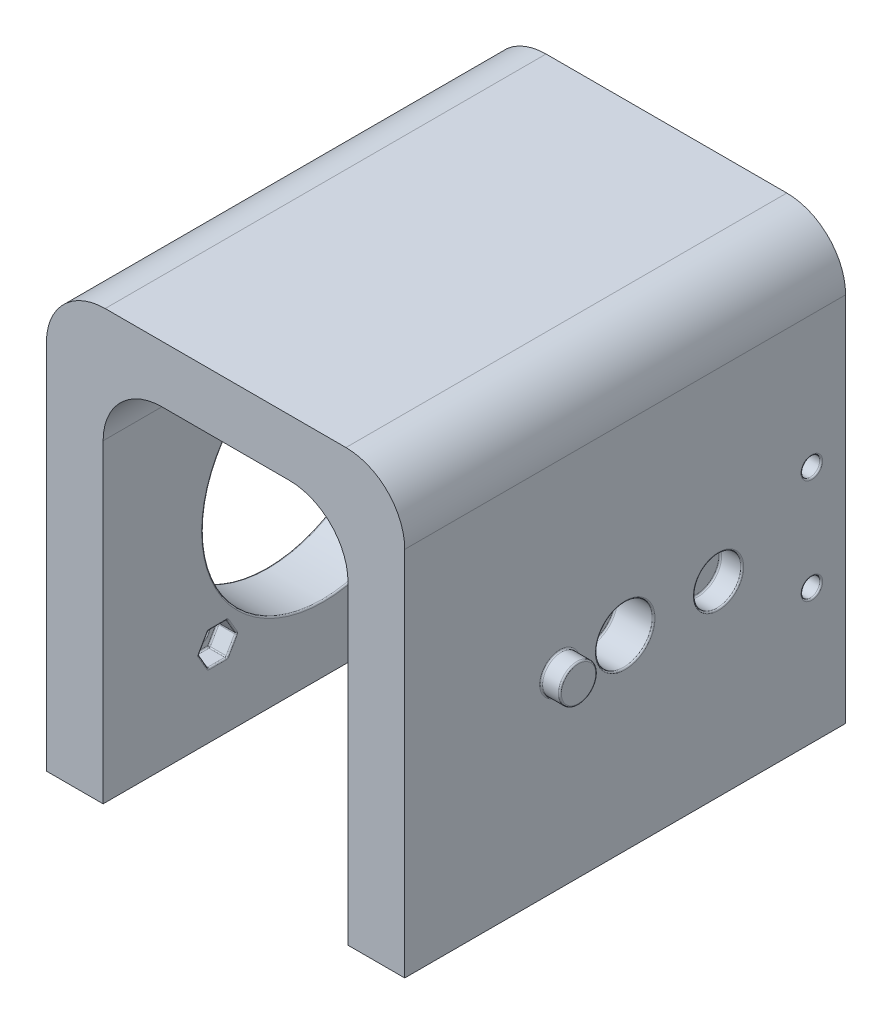
SolidWorks part; units mm, degrees
ref_plane "Front Plane" through (0, 0, 0) normal (0, 0, 1) x (1, 0, 0)
ref_plane "Top Plane" through (0, 0, 0) normal (0, 1, 0) x (1, 0, 0)
ref_plane "Right Plane" through (0, 0, 0) normal (1, 0, 0) x (0, 0, -1)
sketch "Sketch1" plane through (0, 0, 0) normal (0, 0, 1) x (1, 0, 0)
  line L0 (-20.828, 63.5) -> (20.828, 63.5)
  line L1 (20.828, 63.5) -> (20.828, 0)
  line L2 (20.828, 0) -> (30.48, 0)
  line L3 (30.48, 0) -> (30.48, 73.152)
  line L4 (30.48, 73.152) -> (-30.48, 73.152)
  line L5 (-30.48, 73.152) -> (-30.48, 0)
  line L6 (-30.48, 0) -> (-20.828, 0)
  line L7 (-20.828, 0) -> (-20.828, 63.5)
  line L8 (-20.828, 63.5) -> (-20.828, 73.152) construction
  point P2 (0, 63.5)
  point P10 (0, 73.152)
  dimension "D1" = 9.652
  dimension "D2" = 41.656
  dimension "D3" = 63.5
extrude "Boss-Extrude1" add sketch "Sketch1" along normal blind 75
sketch "Sketch2" plane through (-30.48, 0, 0) normal (-1, 0, 0) x (0, 0, 1)
  line L0 (75, 0) -> (0, 0) construction
  line L1 (75, 63.5) -> (0, 63.5) construction
  circle A0 centre (37.5, 31.75) radius 20.5
  point P4 (0, 0)
  point P5 (37.5, 0)
  dimension "D1" = 41
  dimension "D2" = 31.75
extrude "Cut-Extrude1" cut sketch "Sketch2" against normal up to next
sketch "Sketch3" plane through (-30.48, 0, 0) normal (-1, 0, 0) x (0, 0, 1)
  line L1 (19.5, 13.75) -> (55.5, 13.75) construction
  line L2 (19.5, 13.75) -> (19.5, 49.75) construction
  line L3 (19.5, 49.75) -> (55.5, 49.75) construction
  line L4 (55.5, 13.75) -> (55.5, 49.75) construction
  line L5 (19.5, 13.75) -> (55.5, 49.75) construction
  line L6 (19.5, 49.75) -> (55.5, 13.75) construction
  circle A0 centre (37.5, 31.75) radius 20.5 construction
  circle A1 centre (19.5, 49.75) radius 1.5875
  circle A2 centre (55.5, 49.75) radius 1.5875
  circle A3 centre (55.5, 13.75) radius 1.5875
  circle A4 centre (19.5, 13.75) radius 1.5875
  point P0 (37.5, 31.75)
  dimension "D2" = 3.175
  dimension "D1" = 36
extrude "Cut-Extrude2" cut sketch "Sketch3" against normal up to next
sketch "Sketch4" plane through (20.828, 0, 0) normal (-1, 0, 0) x (0, 0, 1)
  circle A0 centre (37.5, 31.75) radius 3.429
  circle A1 centre (37.5, 31.75) radius 20.5 construction
  dimension "D1" = 6.858
extrude "Cut-Extrude3" cut sketch "Sketch4" against normal up to next
sketch "Sketch5" plane through (20.828, 0, 0) normal (-1, 0, 0) x (0, 0, 1)
  circle A0 centre (37.5, 31.75) radius 4.7625
  circle A1 centre (37.5, 31.75) radius 3.429
  circle A2 centre (37.5, 31.75) radius 3.429 construction
  dimension "D1" = 9.525
extrude "Boss-Extrude2" add sketch "Sketch5" along normal blind 1.5875
sketch "Sketch6" plane through (30.48, 0, 0) normal (1, 0, 0) x (0, 0, -1)
  line L0 (-5.75, 40.64) -> (-5.75, 22.86) construction
  line L1 (-37.5, 31.75) -> (-5.75, 31.75) construction
  circle A0 centre (-5.75, 40.64) radius 1.5875
  circle A1 centre (-5.75, 22.86) radius 1.5875
  dimension "D1" = 3.175
  dimension "D2" = 31.75
  dimension "D3" = 8.89
extrude "Cut-Extrude5" cut sketch "Sketch6" against normal up to next
sketch "Sketch7" plane through (30.48, 0, 0) normal (1, 0, 0) x (0, 0, -1)
  line L0 (-37.5, 31.75) -> (-21.625, 31.75) construction
  circle A0 centre (-21.625, 31.75) radius 4.0323
  dimension "D1" = 8.0645
  dimension "D2" = 15.875
extrude "Cut-Extrude6" cut sketch "Sketch7" against normal blind 3.75
sketch "Sketch8" plane through (30.48, 0, 0) normal (1, 0, 0) x (0, 0, -1)
  circle A0 centre (-37.5, 31.75) radius 4.826
  dimension "D1" = 9.652
extrude "Cut-Extrude7" cut sketch "Sketch8" against normal blind 6.35
sketch "Sketch9" plane through (30.48, 0, 0) normal (1, 0, 0) x (0, 0, -1)
  line L0 (-48.6125, 31.75) -> (-37.5, 31.75) construction
  circle A0 centre (-48.6125, 31.75) radius 3.175
  dimension "D1" = 6.35
  dimension "D2" = 11.1125
extrude "Boss-Extrude3" add sketch "Sketch9" along normal blind 3.175
sketch "Sketch10" plane through (20.828, 0, 0) normal (-1, 0, 0) x (0, 0, 1)
  line L1 (8.925, 40.64) -> (7.3375, 43.3896)
  line L2 (7.3375, 43.3896) -> (4.1625, 43.3896)
  line L3 (4.1625, 43.3896) -> (2.575, 40.64)
  line L4 (2.575, 40.64) -> (4.1625, 37.8904)
  line L5 (4.1625, 37.8904) -> (7.3375, 37.8904)
  line L6 (7.3375, 37.8904) -> (8.925, 40.64)
  line L7 (8.925, 22.86) -> (7.3375, 25.6096)
  line L8 (7.3375, 25.6096) -> (4.1625, 25.6096)
  line L9 (4.1625, 25.6096) -> (2.575, 22.86)
  line L10 (2.575, 22.86) -> (4.1625, 20.1104)
  line L11 (4.1625, 20.1104) -> (7.3375, 20.1104)
  line L12 (7.3375, 20.1104) -> (8.925, 22.86)
  circle A0 centre (5.75, 40.64) radius 2.7496 construction
  circle A1 centre (5.75, 22.86) radius 2.7496 construction
  circle A2 centre (5.75, 40.64) radius 1.5875 construction
  circle A3 centre (5.75, 22.86) radius 1.5875 construction
  point P9 (0, 0)
  point P19 (0, 0)
  point P20 (0, 0)
  point P23 (0, 0)
  dimension "D1" = 6.35
extrude "Cut-Extrude8" cut sketch "Sketch10" against normal blind 3.175
sketch "Sketch11" plane through (-30.48, 0, 0) normal (-1, 0, 0) x (0, 0, 1)
  circle A0 centre (19.5, 49.75) radius 2.55
  circle A1 centre (55.5, 49.75) radius 2.55
  circle A2 centre (55.5, 13.75) radius 2.55
  circle A3 centre (19.5, 13.75) radius 2.55
  circle A4 centre (19.5, 49.75) radius 1.5875
  circle A5 centre (55.5, 49.75) radius 1.5875
  circle A6 centre (55.5, 13.75) radius 1.5875
  circle A7 centre (19.5, 13.75) radius 1.5875
  circle A8 centre (19.5, 49.75) radius 1.5875 construction
  circle A9 centre (55.5, 49.75) radius 1.5875 construction
  circle A10 centre (55.5, 13.75) radius 1.5875 construction
  circle A11 centre (19.5, 13.75) radius 1.5875 construction
  dimension "D1" = 5.1
extrude "Boss-Extrude4" add sketch "Sketch11" along normal blind 4.8
sketch "Sketch12" plane through (-20.828, 0, 0) normal (1, 0, 0) x (0, 0, -1)
  line L1 (-16.325, 49.75) -> (-17.9125, 52.4996)
  line L2 (-17.9125, 52.4996) -> (-21.0875, 52.4996)
  line L3 (-21.0875, 52.4996) -> (-22.675, 49.75)
  line L4 (-22.675, 49.75) -> (-21.0875, 47.0004)
  line L5 (-21.0875, 47.0004) -> (-17.9125, 47.0004)
  line L6 (-17.9125, 47.0004) -> (-16.325, 49.75)
  line L7 (-16.325, 13.75) -> (-17.9125, 16.4996)
  line L8 (-17.9125, 16.4996) -> (-21.0875, 16.4996)
  line L9 (-21.0875, 16.4996) -> (-22.675, 13.75)
  line L10 (-22.675, 13.75) -> (-21.0875, 11.0004)
  line L11 (-21.0875, 11.0004) -> (-17.9125, 11.0004)
  line L12 (-17.9125, 11.0004) -> (-16.325, 13.75)
  line L13 (-52.325, 13.75) -> (-53.9125, 16.4996)
  line L14 (-53.9125, 16.4996) -> (-57.0875, 16.4996)
  line L15 (-57.0875, 16.4996) -> (-58.675, 13.75)
  line L16 (-58.675, 13.75) -> (-57.0875, 11.0004)
  line L17 (-57.0875, 11.0004) -> (-53.9125, 11.0004)
  line L18 (-53.9125, 11.0004) -> (-52.325, 13.75)
  line L19 (-52.325, 49.75) -> (-53.9125, 52.4996)
  line L20 (-53.9125, 52.4996) -> (-57.0875, 52.4996)
  line L21 (-57.0875, 52.4996) -> (-58.675, 49.75)
  line L22 (-58.675, 49.75) -> (-57.0875, 47.0004)
  line L23 (-57.0875, 47.0004) -> (-53.9125, 47.0004)
  line L24 (-53.9125, 47.0004) -> (-52.325, 49.75)
  circle A0 centre (-19.5, 49.75) radius 2.7496 construction
  circle A1 centre (-19.5, 13.75) radius 2.7496 construction
  circle A2 centre (-55.5, 13.75) radius 2.7496 construction
  circle A3 centre (-55.5, 49.75) radius 2.7496 construction
  point P28 (0, 0)
  point P37 (0, 0)
  point P38 (0, 0)
  point P39 (0, 0)
  point P40 (0, 0)
  point P42 (0, 0)
  dimension "D1" = 6.35
extrude "Cut-Extrude9" cut sketch "Sketch12" against normal blind 3.175
fillet "Fillet1" radius 10 4 edges at (30.48, 73.152, 37.5) (-30.48, 73.152, 37.5) (20.828, 63.5, 37.5) (-20.828, 63.5, 37.5)
fillet "Fillet2" radius 0.25 27 edges at (19.2405, 31.75, 40.929) (24.003, 22.86, 7.3375) (30.48, 24.4475, 5.75) (24.003, 40.64, 7.3375) (30.48, 42.2275, 5.75) (30.48, 35.7823, 21.625) (26.73, 35.7823, 21.625) (-20.828, 31.75, 58) (30.48, 36.576, 37.5) (24.13, 36.576, 37.5) (33.655, 34.925, 48.6125) (30.48, 28.575, 48.6125) (20.828, 31.75, 32.7375) (19.2405, 31.75, 42.2625) (-30.48, 16.3, 55.5) (-35.28, 11.2, 55.5) (-35.28, 12.1625, 55.5) (-30.48, 16.3, 19.5) (-35.28, 12.1625, 19.5) (-35.28, 11.2, 19.5) (-30.48, 11.25, 37.5) (-30.48, 52.3, 55.5) (-35.28, 48.1625, 55.5) (-30.48, 52.3, 19.5) (-35.28, 48.1625, 19.5) (-35.28, 47.2, 19.5) (-35.28, 47.2, 55.5)
fillet "Fillet3" radius 0.25 112 edges at (20.828, 21.4852, 8.1312) (20.828, 25.6096, 5.75) (20.828, 21.4852, 3.3688) (20.828, 42.0148, 3.3687) (20.828, 37.8904, 5.75) (20.828, 42.0148, 8.1312) (-20.828, 12.3752, 17.1188) (-20.828, 16.4996, 19.5) (-20.828, 12.3752, 21.8812) (-20.828, 12.3752, 57.8812) (-20.828, 12.3752, 53.1188) (-20.828, 16.4996, 55.5) (-20.828, 48.3752, 57.8812) (-20.828, 48.3752, 53.1187) (-20.828, 52.4996, 55.5) (-20.828, 48.3752, 17.1188) (-20.828, 48.3752, 21.8812) (22.4155, 20.1104, 4.1625) (22.4155, 20.1104, 7.3375) (20.828, 20.1104, 5.75) (22.4155, 22.86, 8.925) (22.4155, 25.6096, 7.3375) (20.828, 24.2348, 8.1312) (22.4155, 25.6096, 4.1625) (22.4155, 22.86, 2.575) (20.828, 24.2348, 3.3688) (24.003, 20.1104, 5.75) (24.003, 21.4852, 3.3688) (24.003, 24.2348, 3.3688) (24.003, 25.6096, 5.75) (24.003, 24.2348, 8.1312) (24.003, 21.4852, 8.1312) (22.4155, 40.64, 2.575) (22.4155, 37.8904, 4.1625) (20.828, 39.2652, 3.3688) (22.4155, 43.3896, 7.3375) (22.4155, 43.3896, 4.1625) (20.828, 43.3896, 5.75) (22.4155, 37.8904, 7.3375) (22.4155, 40.64, 8.925) (20.828, 39.2652, 8.1313) (24.003, 37.8904, 5.75) (24.003, 39.2652, 3.3688) (24.003, 42.0148, 3.3687) (24.003, 43.3896, 5.75) (24.003, 42.0148, 8.1312) (24.003, 39.2652, 8.1313) (-22.4155, 11.0004, 21.0875) (-22.4155, 11.0004, 17.9125) (-20.828, 11.0004, 19.5) (-22.4155, 13.75, 16.325) (-22.4155, 16.4996, 17.9125) (-20.828, 15.1248, 17.1188) (-22.4155, 16.4996, 21.0875) (-22.4155, 13.75, 22.675) (-20.828, 15.1248, 21.8812) (-24.003, 13.75, 17.9125) (-24.003, 11.0004, 19.5) (-24.003, 12.3752, 21.8812) (-24.003, 15.1248, 21.8812) (-24.003, 16.4996, 19.5) (-24.003, 15.1248, 17.1188) (-24.003, 12.3752, 17.1188) (-22.4155, 16.4996, 57.0875) (-22.4155, 13.75, 58.675) (-20.828, 15.1248, 57.8812) (-22.4155, 11.0004, 57.0875) (-22.4155, 11.0004, 53.9125) (-20.828, 11.0004, 55.5) (-22.4155, 13.75, 52.325) (-22.4155, 16.4996, 53.9125) (-20.828, 15.1248, 53.1187) (-24.003, 13.75, 53.9125) (-24.003, 11.0004, 55.5) (-24.003, 12.3752, 57.8812) (-24.003, 15.1248, 57.8812) (-24.003, 16.4996, 55.5) (-24.003, 15.1248, 53.1187) (-24.003, 12.3752, 53.1188) (-22.4155, 47.0004, 57.0875) (-22.4155, 47.0004, 53.9125) (-20.828, 47.0004, 55.5) (-22.4155, 52.4996, 57.0875) (-22.4155, 49.75, 58.675) (-20.828, 51.1248, 57.8812) (-22.4155, 49.75, 52.325) (-22.4155, 52.4996, 53.9125) (-20.828, 51.1248, 53.1187) (-24.003, 49.75, 53.9125) (-24.003, 47.0004, 55.5) (-24.003, 48.3752, 57.8812) (-24.003, 51.1248, 57.8812) (-24.003, 52.4996, 55.5) (-24.003, 51.1248, 53.1187) (-24.003, 48.3752, 53.1187) (-22.4155, 49.75, 16.325) (-20.828, 51.1248, 17.1187) (-22.4155, 47.0004, 21.0875) (-22.4155, 47.0004, 17.9125) (-20.828, 47.0004, 19.5) (-22.4155, 52.4996, 17.9125) (-20.828, 52.4996, 19.5) (-22.4155, 52.4996, 21.0875) (-22.4155, 49.75, 22.675) (-20.828, 51.1248, 21.8812) (-24.003, 49.75, 17.9125) (-24.003, 47.0004, 19.5) (-24.003, 48.3752, 21.8812) (-24.003, 51.1248, 21.8812) (-24.003, 52.4996, 19.5) (-24.003, 51.1248, 17.1187) (-24.003, 48.3752, 17.1188)
